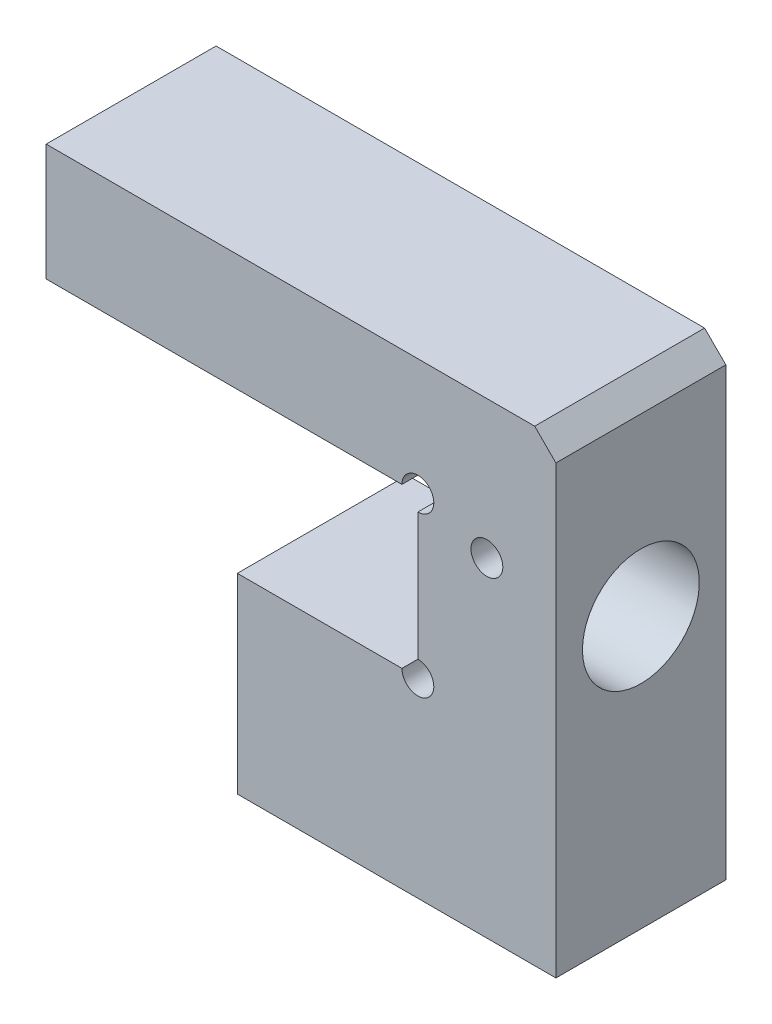
SolidWorks part; units mm, degrees
material "AISI 1045 Aço, trefilado"
ref_plane "Plano frontal" through (0, 0, 0) normal (0, 0, 1) x (1, 0, 0)
ref_plane "Plano superior" through (0, 0, 0) normal (0, 1, 0) x (1, 0, 0)
ref_plane "Plano direito" through (0, 0, 0) normal (1, 0, 0) x (0, 0, -1)
sketch "Esboço1" plane through (0, 0, 0) normal (0, 0, 1) x (1, 0, 0)
  line L0 (0, 0) -> (48, 0)
  line L1 (48, 0) -> (48, -44)
  line L2 (0, 0) -> (0, -11)
  line L3 (0, -11) -> (35, -11)
  line L4 (35, -11) -> (35, -26)
  line L5 (35, -26) -> (18, -26)
  line L6 (18, -26) -> (18, -44)
  line L7 (18, -44) -> (48, -44)
  circle A0 centre (35, -11) radius 1.5
  circle A1 centre (35, -26) radius 1.5
  circle A2 centre (41.5, -13) radius 1.5
  dimension "D7" = 3
  dimension "D8" = 6.5
  dimension "D1" = 48
  dimension "D2" = 33
  dimension "D3" = 18
  dimension "D4" = 13
  dimension "D5" = 44
  dimension "D6" = 30
  dimension "D9" = 2
extrude "Ressalto-extrusão1" add sketch "Esboço1" along normal blind 16 contours A1 L5 L6 L7 L1 L0 L2 L3 A0 L4 A2
chamfer "Chanfro1" distance 2 angle 45 1 edges at (48, 0, 8)
sketch "Esboço2" plane through (35, 0, 0) normal (-1, 0, 0) x (0, 0, 1)
  line L0 (0, 0) -> (0, -11) construction
  line L1 (16, -11) -> (0, -11) construction
  circle A0 centre (8, -18.5) radius 5.5
  dimension "D1" = 11
  dimension "D2" = 8
  dimension "D3" = 7.5
extrude "Corte-extrusão1" cut sketch "Esboço2" against normal through all
sketch "Esboço5" plane through (0, -44, 0) normal (0, -1, 0) x (1, 0, 0)
  line L0 (48, 16) -> (48, 0) construction
  circle A0 centre (41.5, 8) radius 3
  dimension "D1" = 6
  dimension "D2" = 6.5
extrude "Corte-extrusão2" cut sketch "Esboço5" against normal blind 16
